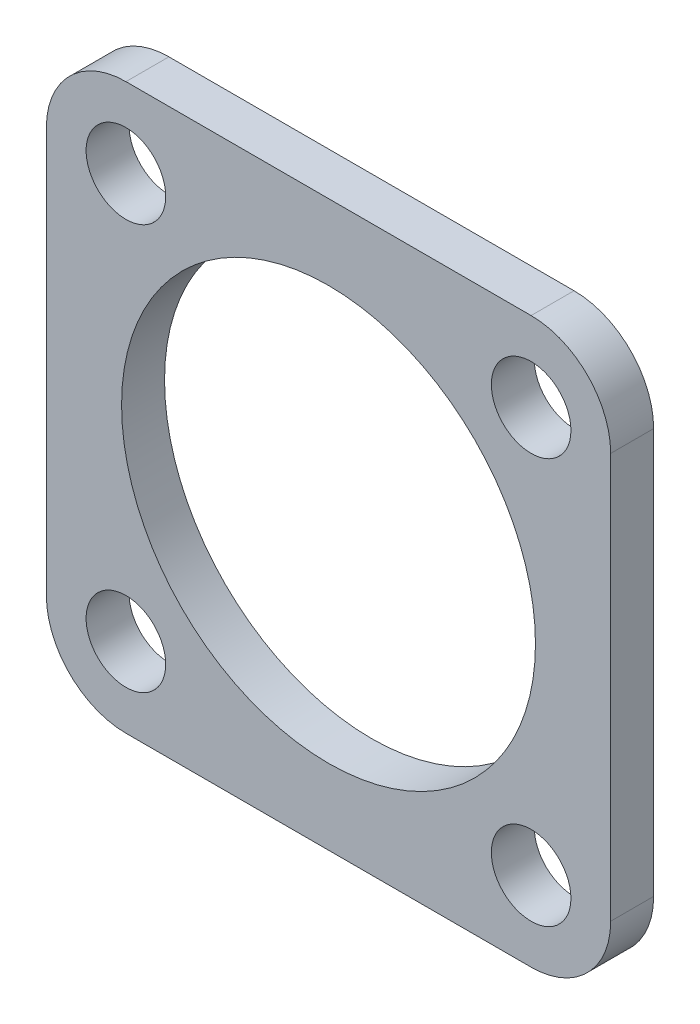
SolidWorks part; units mm, degrees
ref_plane "Front Plane" through (0, 0, 0) normal (0, 0, 1) x (1, 0, 0)
ref_plane "Top Plane" through (0, 0, 0) normal (0, 1, 0) x (1, 0, 0)
ref_plane "Right Plane" through (0, 0, 0) normal (1, 0, 0) x (0, 0, -1)
sketch "Sketch1" plane through (0, 0, 0) normal (0, 0, 1) x (1, 0, 0)
  line L0 (35.45, 70.9) -> (35.45, -3.9902) construction
  line L1 (0, 0) -> (70.9, 0)
  line L2 (0, 0) -> (0, 70.9)
  line L3 (0, 70.9) -> (70.9, 70.9)
  line L4 (70.9, 0) -> (70.9, 70.9)
  line L5 (0, 35.45) -> (101.4833, 35.45) construction
  circle A0 centre (9.995, 60.905) radius 5
  circle A1 centre (60.905, 60.905) radius 5
  circle A2 centre (60.905, 9.995) radius 5
  circle A3 centre (9.995, 9.995) radius 5
  circle A4 centre (35.45, 35.45) radius 26
  dimension "D2" = 10
  dimension "D5" = 52
  dimension "D1" = 70.9
  dimension "D3" = 50.91
  dimension "D4" = 50.91
extrude "Boss-Extrude1" add sketch "Sketch1" along normal blind 5 and the other way blind 0.3972
fillet "Fillet1" radius 10 4 edges at (70.9, 0, 2.3014) (0, 0, 2.3014) (0, 70.9, 2.3014) (70.9, 70.9, 2.3014)
